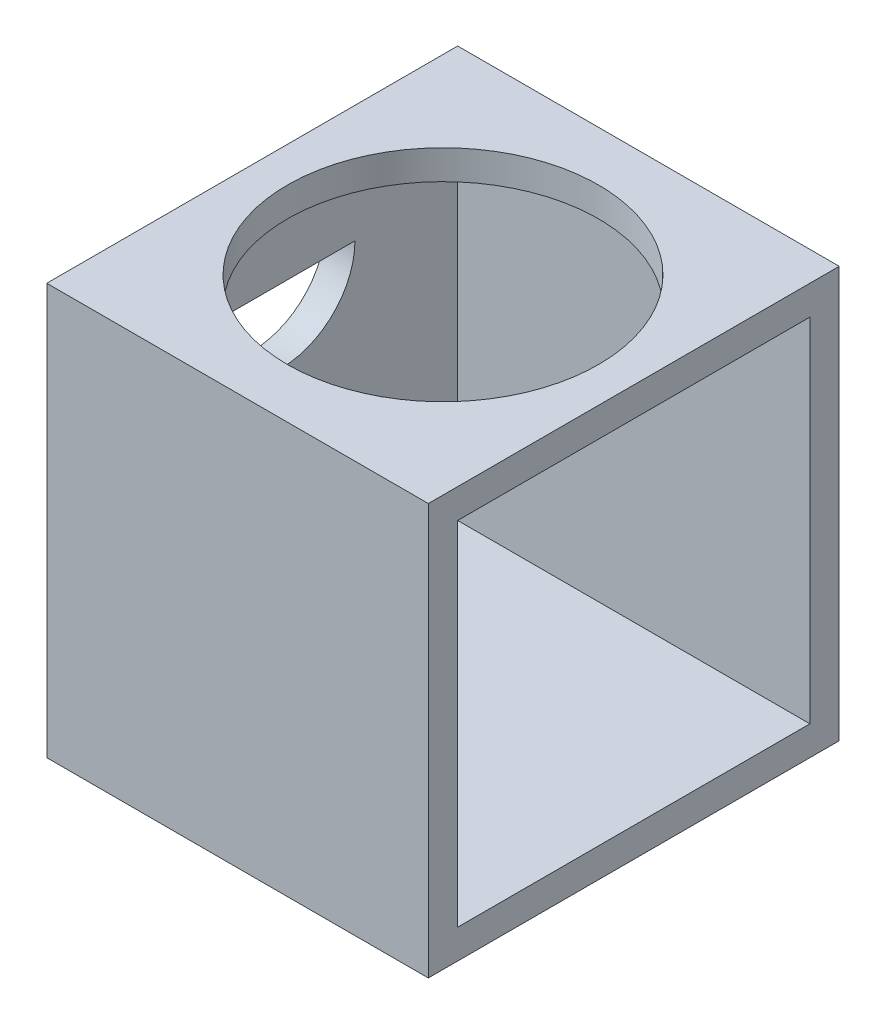
SolidWorks part; units mm, degrees
ref_plane "Front Plane" through (0, 0, 0) normal (0, 0, 1) x (1, 0, 0)
ref_plane "Top Plane" through (0, 0, 0) normal (0, 1, 0) x (1, 0, 0)
ref_plane "Right Plane" through (0, 0, 0) normal (1, 0, 0) x (0, 0, -1)
sketch "Sketch2" plane through (0, 0, 0) normal (1, 0, 0) x (0, 0, -1)
  line L1 (-60, 60) -> (60, 60)
  line L2 (-60, 60) -> (-60, -60)
  line L3 (-60, -60) -> (60, -60)
  line L4 (60, 60) -> (60, -60)
  line L5 (-60, 60) -> (60, -60) construction
  line L6 (-60, -60) -> (60, 60) construction
  point P0 (0, 0)
  dimension "D1" = 120
extrude "Extrude-Thin1" add sketch "Sketch2" along normal blind 120 thin contours L2 L1 L4 L3 thin type one direction wall 10
sketch "Sketch3" plane through (0, 0, 0) normal (-1, 0, 0) x (0, 0, 1)
  line L1 (-70, 70) -> (70, 70)
  line L2 (-70, 70) -> (-70, -70)
  line L3 (-70, -70) -> (70, -70)
  line L4 (70, 70) -> (70, -70)
extrude "Boss-Extrude1" add sketch "Sketch3" along normal blind 10
sketch "Sketch5" plane through (0, 70, 0) normal (0, 1, 0) x (1, 0, 0)
  line L1 (-10, 70) -> (120, 70) construction
  line L2 (-10, 70) -> (-10, -70) construction
  line L3 (-10, -70) -> (120, -70) construction
  line L4 (120, 70) -> (120, -70) construction
  line L5 (-10, 70) -> (120, -70) construction
  line L6 (-10, -70) -> (120, 70) construction
  circle A0 centre (55, 0) radius 53
  point P0 (55, 0)
  dimension "D1" = 106
extrude "Cut-Extrude1" cut sketch "Sketch5" against normal up to next contours A0
sketch "Sketch8" plane through (-10, 0, 0) normal (-1, 0, 0) x (0, 0, 1)
  line L0 (-25, 40) -> (25, 40)
  line L1 (-70, 70) -> (70, 70) construction
  arc A0 (-25, 40) -> (25, 40) centre (0, 40) ccw
  point P4 (0, 70)
  point P5 (0, 40)
  dimension "D1" = 25
  dimension "D2" = 30
extrude "Cut-Extrude4" cut sketch "Sketch8" against normal up to next contours L0 A0
sketch "Sketch9" plane through (0, 70, 0) normal (0, 1, 0) x (1, 0, 0)
  line L0 (-10, 70) -> (120, 70) construction
  line L1 (55, 70) -> (55, -70) construction
  line L2 (120, -70) -> (-10, -70) construction
ref_plane "Plane1" through (55, 0, 0) normal (1, 0, 0) x (0, 0, -1)
ref_plane "Plane2" through (42.5, 0, 0) normal (1, 0, 0) x (0, 0, -1)
